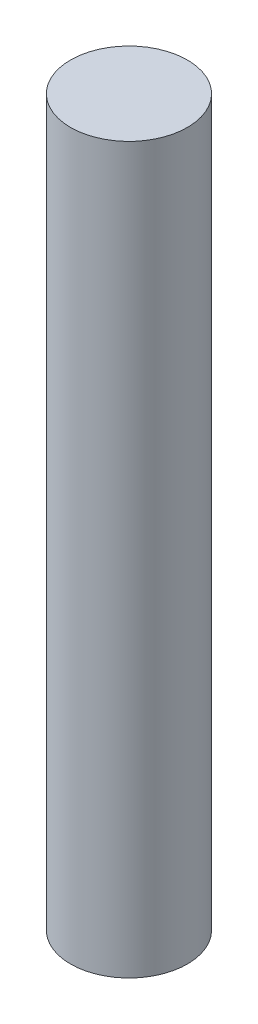
SolidWorks part; units mm, degrees
ref_plane "Front Plane" through (0, 0, 0) normal (0, 0, 1) x (1, 0, 0)
ref_plane "Top Plane" through (0, 0, 0) normal (0, 1, 0) x (1, 0, 0)
ref_plane "Right Plane" through (0, 0, 0) normal (1, 0, 0) x (0, 0, -1)
sketch "Sketch1" plane through (0, 0, 0) normal (0, 1, 0) x (1, 0, 0)
  circle A0 centre (0, 0) radius 2.5
  dimension "D1" = 5
extrude "Boss-Extrude1" add sketch "Sketch1" along normal blind 31
